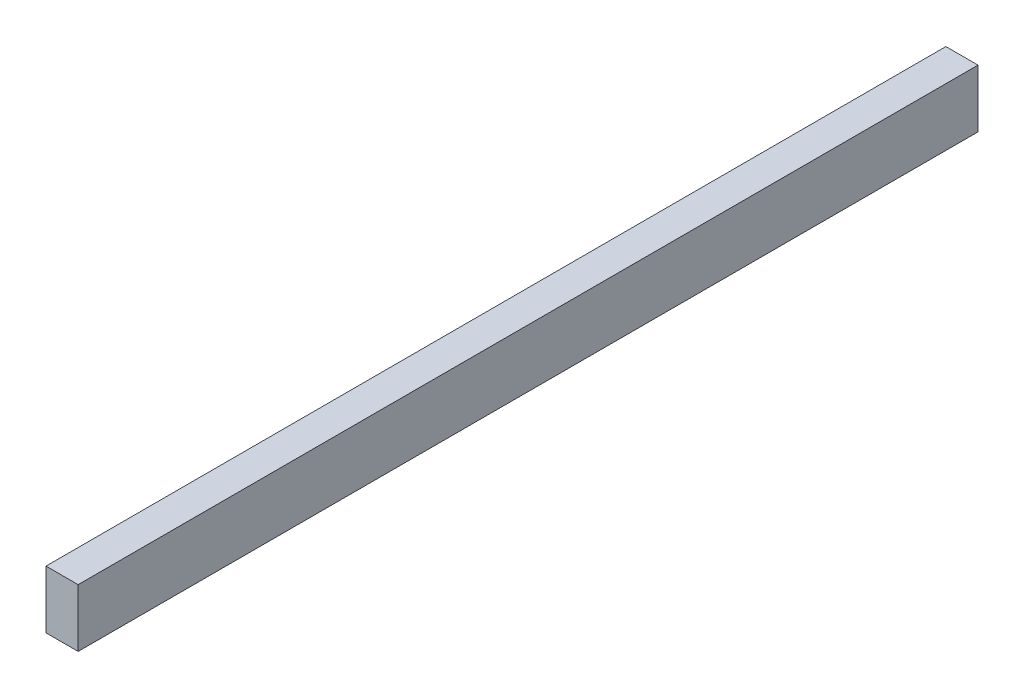
SolidWorks part; units mm, degrees
ref_plane "Plan de face" through (0, 0, 0) normal (0, 0, 1) x (1, 0, 0)
ref_plane "Plan de dessus" through (0, 0, 0) normal (0, 1, 0) x (1, 0, 0)
ref_plane "Plan de droite" through (0, 0, 0) normal (1, 0, 0) x (0, 0, -1)
sketch "Esquisse1" plane through (0, 0, 0) normal (0, 0, 1) x (1, 0, 0)
  line L1 (0, 0) -> (25, 0)
  line L2 (0, 0) -> (0, 45)
  line L3 (0, 45) -> (25, 45)
  line L4 (25, 0) -> (25, 45)
  dimension "D1" = 25
  dimension "D2" = 45
extrude "Boss.-Extru.1" add sketch "Esquisse1" along normal blind 700
